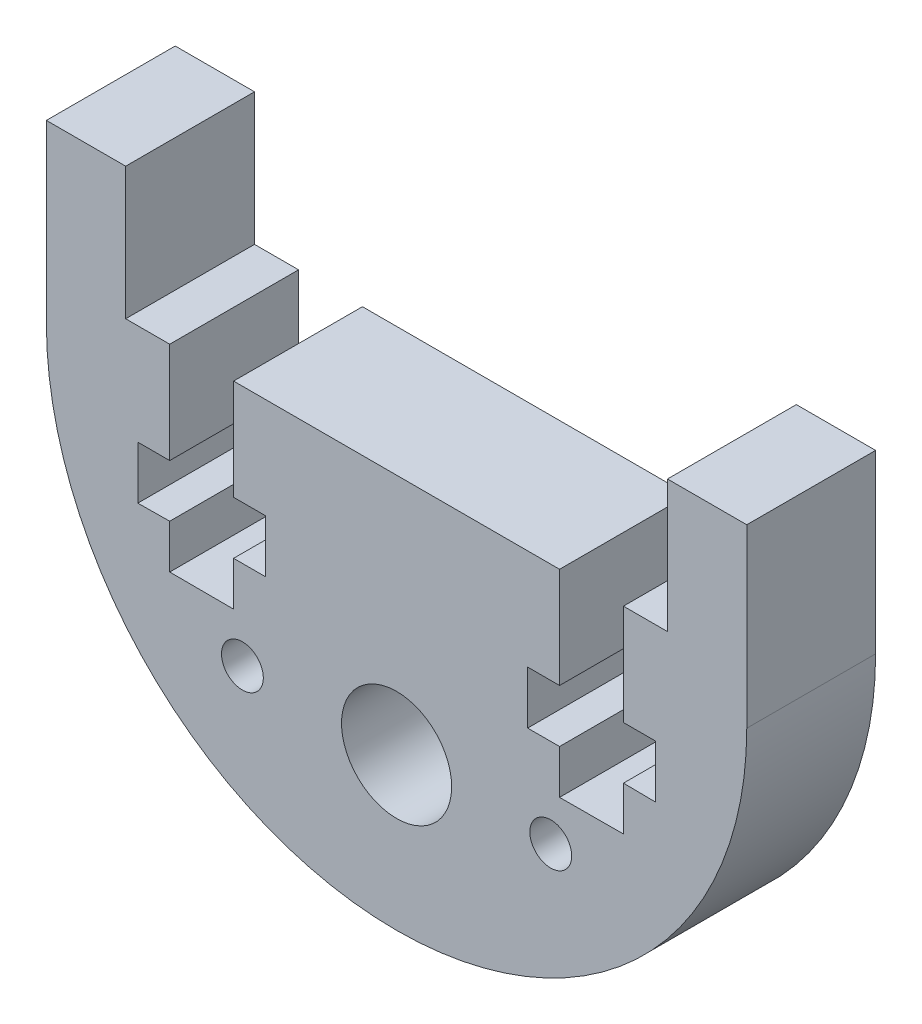
SolidWorks part; units mm, degrees
material "Acrylic (Medium-high impact)"
ref_plane "Front Plane" through (0, 0, 0) normal (0, 0, 1) x (1, 0, 0)
ref_plane "Top Plane" through (0, 0, 0) normal (0, 1, 0) x (1, 0, 0)
ref_plane "Right Plane" through (0, 0, 0) normal (1, 0, 0) x (0, 0, -1)
sketch "Model" plane through (0, 0, 0) normal (0, 0, 1) x (1, 0, 0)
  line L0 (546.1095, 558.5325) -> (553.5095, 558.5325)
  line L1 (553.5095, 547.5325) -> (553.5095, 540.5325) construction
  line L2 (553.5095, 547.5325) -> (553.5095, 540.5325) construction
  line L3 (546.5095, 547.5325) -> (553.5095, 547.5325) construction
  line L4 (560.5095, 547.5325) -> (553.5095, 547.5325) construction
  line L5 (553.5095, -443.4675) -> (553.5095, 49556.5325) construction
  line L6 (553.5095, 547.5325) -> (553.5095, 540.5325) construction
  line L7 (553.5095, 540.5325) -> (553.5095, 547.5325) construction
  line L8 (560.9095, 553.9618) -> (560.9095, 558.5325)
  line L9 (559.4595, 553.9627) -> (560.9095, 553.9618)
  line L10 (559.4595, 551.5626) -> (559.4595, 553.9627)
  line L11 (560.9095, 551.5635) -> (559.4595, 551.5626)
  line L12 (560.9095, 549.5635) -> (560.9095, 551.5635)
  line L13 (563.8096, 549.573) -> (560.9095, 549.5635)
  line L14 (563.8096, 551.573) -> (563.8096, 549.573)
  line L15 (565.2595, 551.5565) -> (563.8096, 551.573)
  line L16 (565.2595, 553.9566) -> (565.2595, 551.5565)
  line L17 (563.8095, 553.9566) -> (565.2595, 553.9566)
  line L18 (563.8095, 558.5325) -> (563.8095, 553.9566)
  line L19 (565.8095, 558.5325) -> (563.8095, 558.5325)
  line L20 (565.8095, 564.5325) -> (565.8095, 558.5325)
  line L21 (569.4095, 564.5325) -> (565.8095, 564.5325)
  line L22 (569.4095, 556.5325) -> (569.4095, 564.5325)
  line L23 (560.9095, 558.5325) -> (553.5095, 558.5325)
  line L24 (553.5095, 547.5325) -> (553.5095, 553.0893) construction
  line L25 (543.2095, 558.5325) -> (546.1095, 558.5325) construction
  line L41 (537.6095, 556.5325) -> (537.6095, 564.5325)
  line L42 (537.6095, 564.5325) -> (541.2095, 564.5325)
  line L43 (541.2095, 564.5325) -> (541.2095, 558.5325)
  line L44 (541.2095, 558.5325) -> (543.2095, 558.5325)
  line L45 (543.2095, 558.5325) -> (543.2095, 553.9566)
  line L46 (543.2095, 553.9566) -> (541.7595, 553.9566)
  line L47 (541.7595, 553.9566) -> (541.7595, 551.5565)
  line L48 (541.7595, 551.5565) -> (543.2094, 551.573)
  line L49 (543.2094, 551.573) -> (543.2094, 549.573)
  line L50 (543.2094, 549.573) -> (546.1095, 549.5635)
  line L51 (546.1095, 549.5635) -> (546.1095, 551.5635)
  line L52 (546.1095, 551.5635) -> (547.5595, 551.5626)
  line L53 (547.5595, 551.5626) -> (547.5595, 553.9627)
  line L54 (547.5595, 553.9627) -> (546.1095, 553.9618)
  line L55 (546.1095, 553.9618) -> (546.1095, 558.5325)
  circle A0 centre (546.5095, 547.5325) radius 0.95
  circle A1 centre (553.5095, 547.5325) radius 2.4999
  arc A4 (569.4095, 556.5325) -> (537.6095, 556.5325) centre (553.5095, 556.5325) cw
  circle A8 centre (560.5095, 547.5325) radius 0.95
  point P7 (544.6595, 558.5325)
  dimension "D10" = 7
  dimension "D9" = 1.9
  dimension "D1" = 3.6
  dimension "D2" = 6
  dimension "D3" = 8
  dimension "D4" = 2.4001
  dimension "D5" = 1.45
  dimension "D6" = 4.5759
  dimension "D7" = 2
  dimension "D8" = 2
  dimension "D11" = 7.4
  dimension "D12" = 11
  dimension "D13" = 2.9
extrude "Boss-Extrude2" add sketch "Model" along normal blind 5.85
